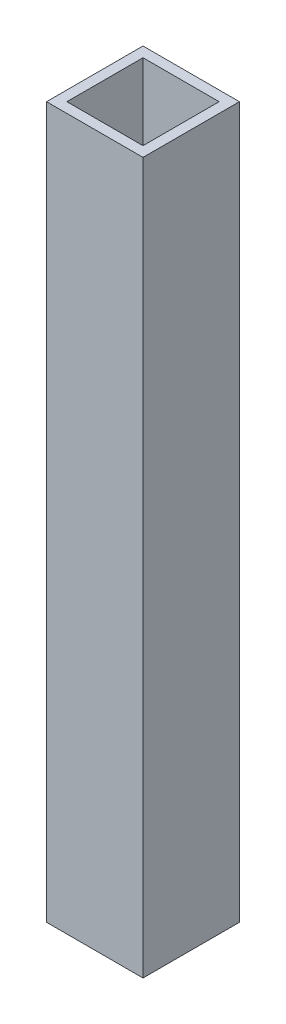
SolidWorks part; units mm, degrees
ref_plane "Front Plane" through (0, 0, 0) normal (0, 0, 1) x (1, 0, 0)
ref_plane "Top Plane" through (0, 0, 0) normal (0, 1, 0) x (1, 0, 0)
ref_plane "Right Plane" through (0, 0, 0) normal (1, 0, 0) x (0, 0, -1)
sketch "Sketch1" plane through (0, 0, 0) normal (0, 1, 0) x (1, 0, 0)
  line L1 (-9.5, -9.5) -> (9.5, -9.5)
  line L2 (-9.5, -9.5) -> (-9.5, 9.5)
  line L3 (-9.5, 9.5) -> (9.5, 9.5)
  line L4 (9.5, -9.5) -> (9.5, 9.5)
  line L5 (-9.5, -9.5) -> (9.5, 9.5) construction
  line L6 (-9.5, 9.5) -> (9.5, -9.5) construction
  point P0 (0, 0)
  dimension "D1" = 19
  dimension "D2" = 19
extrude "Extrude-Thin1" add sketch "Sketch1" along normal blind 140 thin thin type one direction reverse wall 2
